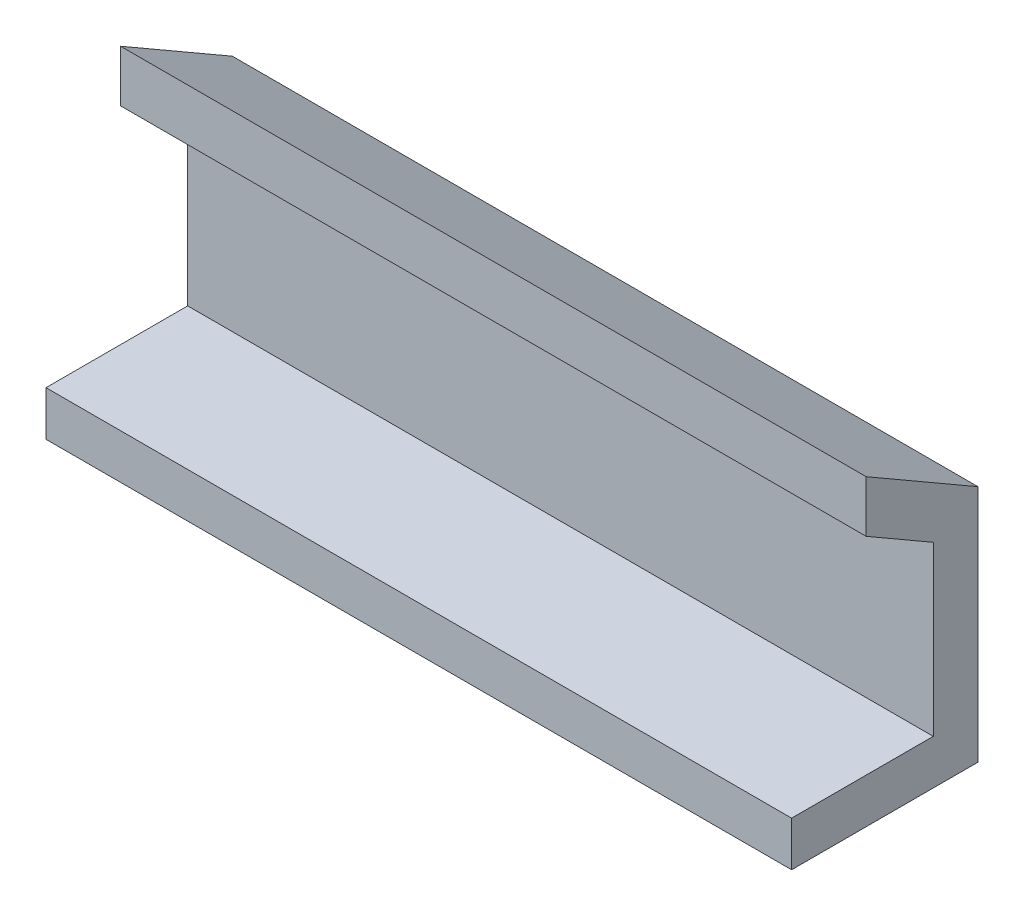
SolidWorks part; units mm, degrees
ref_plane "Спереди" through (0, 0, 0) normal (0, 0, 1) x (1, 0, 0)
ref_plane "Сверху" through (0, 0, 0) normal (0, 1, 0) x (1, 0, 0)
ref_plane "Справа" through (0, 0, 0) normal (1, 0, 0) x (0, 0, -1)
sketch "Эскиз1" plane through (0, 0, 0) normal (1, 0, 0) x (0, 0, -1)
  line L0 (0, 0) -> (25, 0)
  line L1 (25, 0) -> (25, 32)
  line L2 (25, 32) -> (10, 40.6603)
  line L3 (10, 40.6603) -> (10, 33.7321)
  line L4 (10, 33.7321) -> (19, 28.5359)
  line L5 (19, 28.5359) -> (19, 6)
  line L6 (19, 6) -> (0, 6)
  line L7 (0, 6) -> (0, 0)
  dimension "D1" = 25
  dimension "D2" = 32
  dimension "D3" = 6
  dimension "D4" = 60
  dimension "D5" = 6
  dimension "D6" = 6
  dimension "D7" = 15
extrude "Бобышка-Вытянуть1" add sketch "Эскиз1" along normal blind 100
